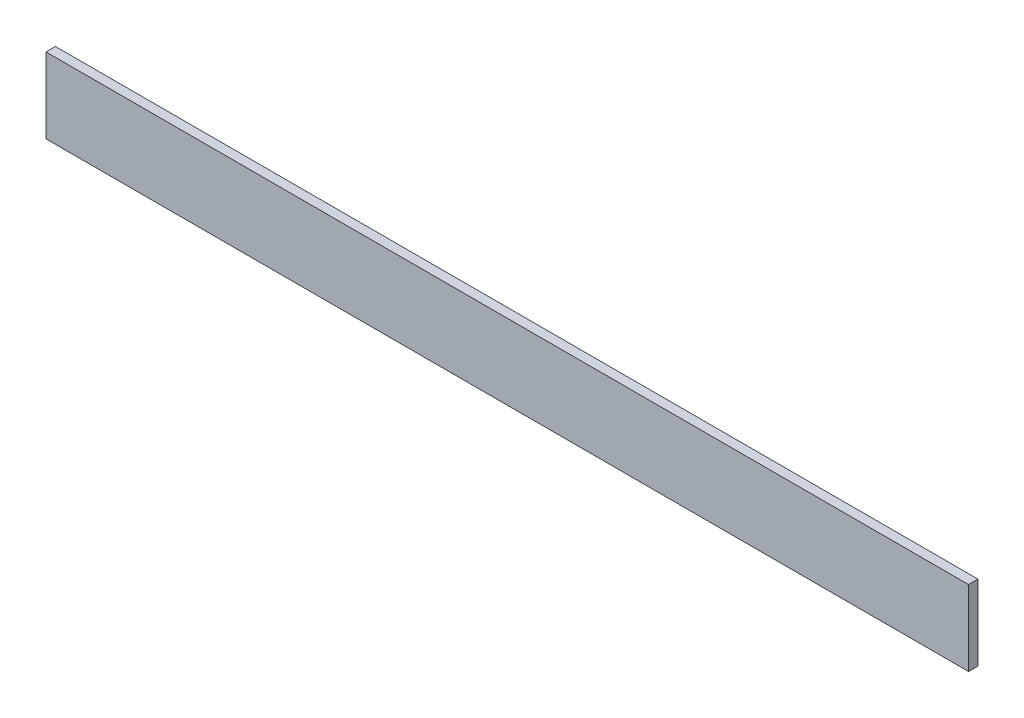
SolidWorks part; units mm, degrees
material "Pine"
ref_plane "Front Plane" through (0, 0, 0) normal (0, 0, 1) x (1, 0, 0)
ref_plane "Top Plane" through (0, 0, 0) normal (0, 1, 0) x (1, 0, 0)
ref_plane "Right Plane" through (0, 0, 0) normal (1, 0, 0) x (0, 0, -1)
sketch "Sketch1" plane through (0, 0, 0) normal (0, 0, 1) x (1, 0, 0)
  line L1 (933.45, -76.2) -> (-933.45, -76.2)
  line L2 (933.45, -76.2) -> (933.45, 76.2)
  line L3 (933.45, 76.2) -> (-933.45, 76.2)
  line L4 (-933.45, -76.2) -> (-933.45, 76.2)
  line L5 (933.45, -76.2) -> (-933.45, 76.2) construction
  line L6 (933.45, 76.2) -> (-933.45, -76.2) construction
  point P0 (0, 0)
  dimension "D1" = 1866.9
  dimension "D2" = 152.4
extrude "Boss-Extrude1" add sketch "Sketch1" along normal blind 19.05
